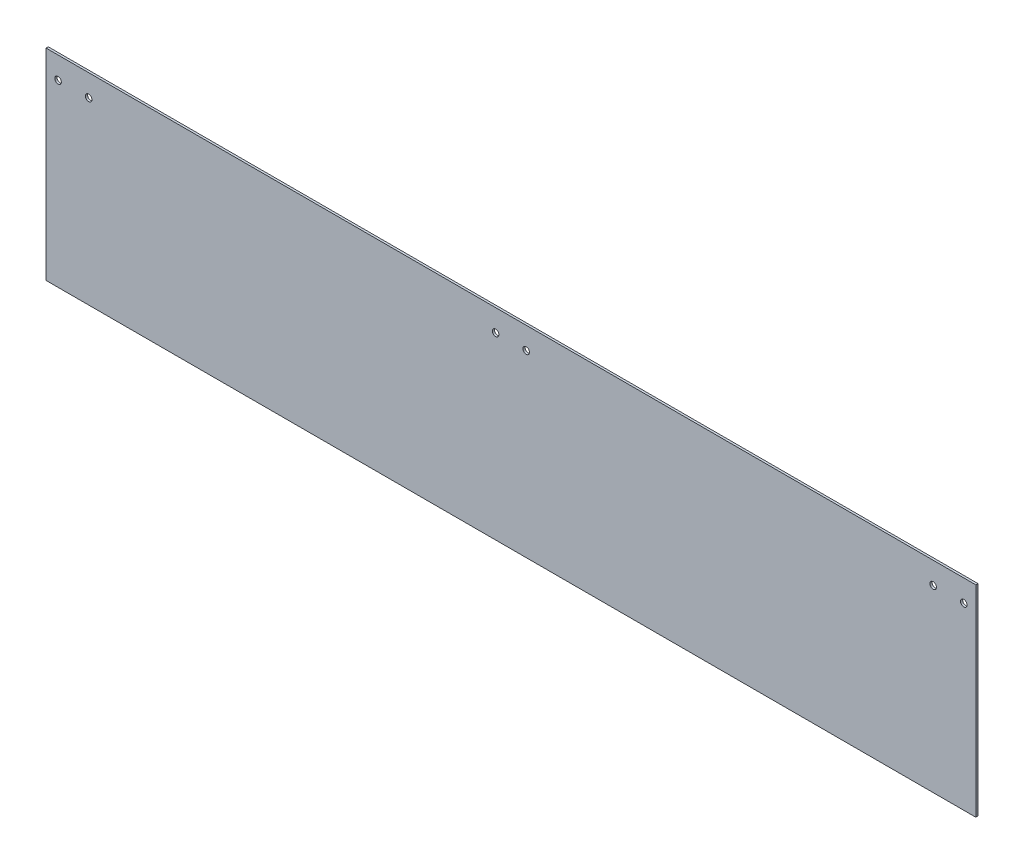
SolidWorks part; units mm, degrees
material "ABS PC"
ref_plane "前视基准面" through (0, 0, 0) normal (0, 0, 1) x (1, 0, 0)
ref_plane "上视基准面" through (0, 0, 0) normal (0, 1, 0) x (1, 0, 0)
ref_plane "右视基准面" through (0, 0, 0) normal (1, 0, 0) x (0, 0, -1)
sketch "草图1" plane through (0, 0, 0) normal (0, 0, 1) x (1, 0, 0)
  line L1 (-212.5, 46) -> (212.5, 46)
  line L2 (-212.5, 46) -> (-212.5, -46)
  line L3 (-212.5, -46) -> (212.5, -46)
  line L4 (212.5, 46) -> (212.5, -46)
  line L5 (-212.5, 46) -> (212.5, -46) construction
  line L6 (-212.5, -46) -> (212.5, 46) construction
  point P0 (0, 0)
  dimension "D1" = 425
  dimension "D2" = 92
extrude "凸台-拉伸1" add sketch "草图1" along normal blind 1
sketch "草图2" plane through (0, 0, 1) normal (0, 0, 1) x (1, 0, 0)
  line L0 (-212.5, 36) -> (212.5, 36) construction
  line L1 (-212.5, 46) -> (-212.5, -46) construction
  line L2 (212.5, -46) -> (212.5, 46) construction
  line L3 (0, 46) -> (0, 36) construction
  line L4 (212.5, 46) -> (-212.5, 46) construction
  circle A0 centre (-7, 36) radius 1.5
  circle A1 centre (-207, 36) radius 1.5
  circle A2 centre (-193, 36) radius 1.5
  circle A3 centre (193, 36) radius 1.5
  circle A4 centre (207, 36) radius 1.5
  circle A5 centre (7, 36) radius 1.5
  dimension "D1" = 3
  dimension "D2" = 14
  dimension "D3" = 10
  dimension "D4" = 193
  dimension "D5" = 7
extrude "切除-拉伸1" cut sketch "草图2" against normal through all
